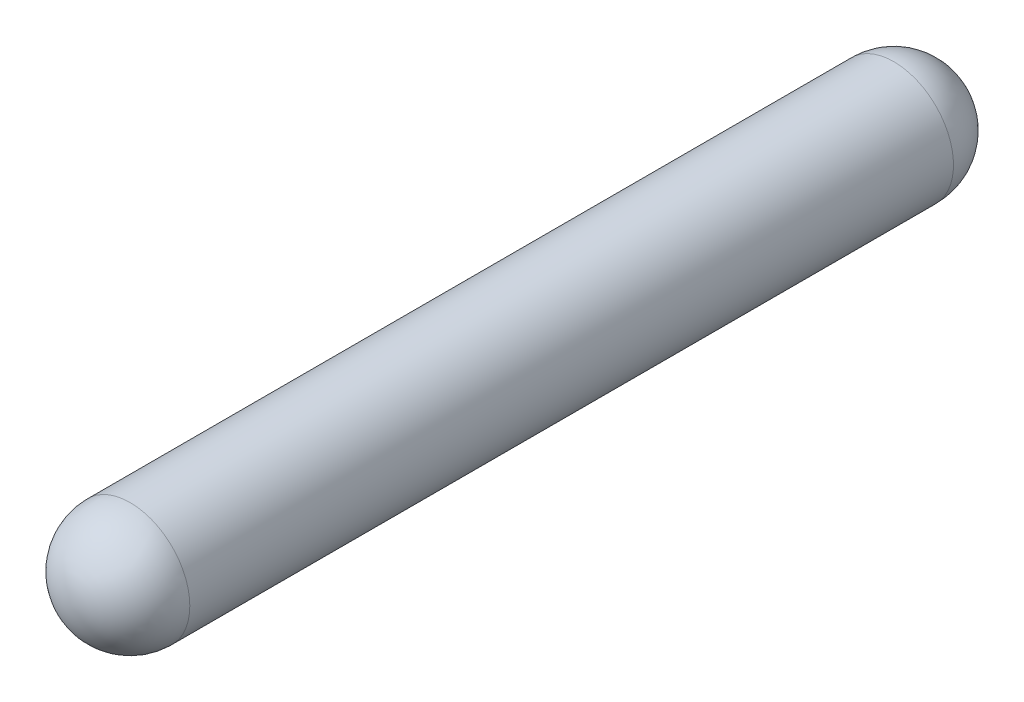
SolidWorks part; units mm, degrees
ref_plane "Ön Düzlem" through (0, 0, 0) normal (0, 0, 1) x (1, 0, 0)
ref_plane "Üst Düzlem" through (0, 0, 0) normal (0, 1, 0) x (1, 0, 0)
ref_plane "Sağ Düzlem" through (0, 0, 0) normal (1, 0, 0) x (0, 0, -1)
ref_plane "Düzlem1" through (0, 0, 0) normal (0, -1, 0) x (1, 0, 0)
sketch "Çizim1" plane through (0, 0, 0) normal (0, -1, 0) x (1, 0, 0)
  line L0 (0, 37) -> (0, 0)
  line L1 (2.5, 2.5) -> (2.5, 34.5)
  line L2 (0, 37) -> (0, 0) construction
  arc A0 (2.5, 34.5) -> (0, 37) centre (0, 34.5) ccw
  arc A1 (0, 0) -> (2.5, 2.5) centre (0, 2.5) ccw
revolve "Döndür1" add sketch "Çizim1" angle 360 about L2
